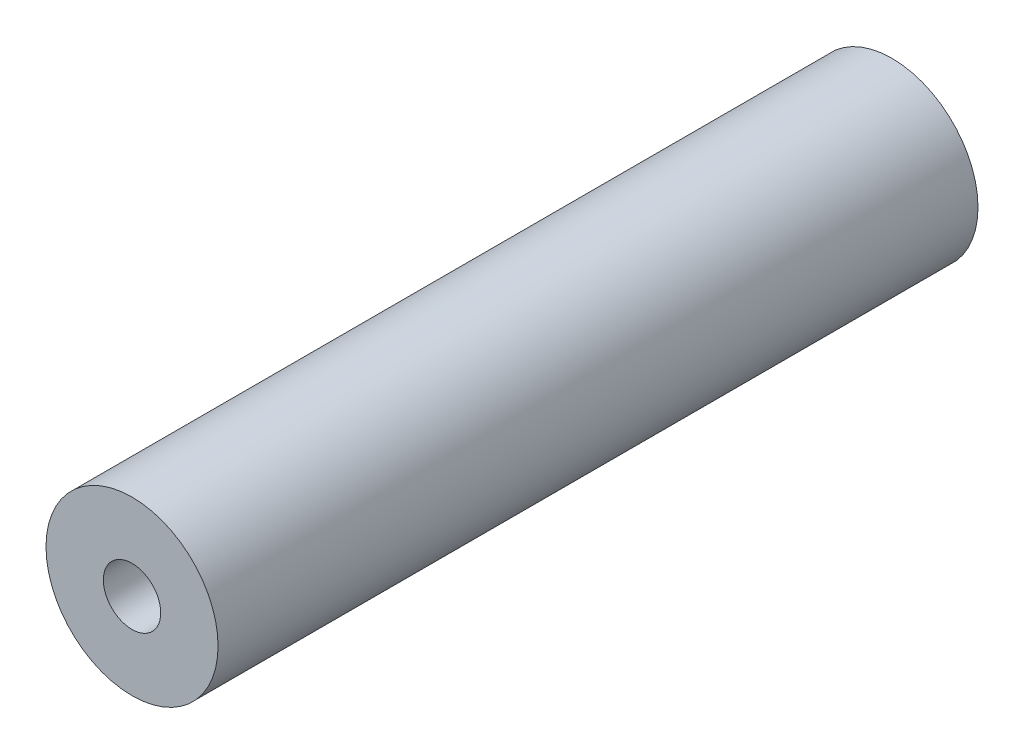
SolidWorks part; units mm, degrees
material "Нержавеющая сталь (ферритная)"
ref_plane "Спереди" through (0, 0, 0) normal (0, 0, 1) x (1, 0, 0)
ref_plane "Сверху" through (0, 0, 0) normal (0, 1, 0) x (1, 0, 0)
ref_plane "Справа" through (0, 0, 0) normal (1, 0, 0) x (0, 0, -1)
sketch "Эскиз1" plane through (0, 0, 0) normal (0, 0, 1) x (1, 0, 0)
  circle A0 centre (0, 0) radius 3
  circle A1 centre (0, 0) radius 1
  dimension "D1" = 6
  dimension "D2" = 2
extrude "Бобышка-Вытянуть1" add sketch "Эскиз1" along normal blind 26.5
